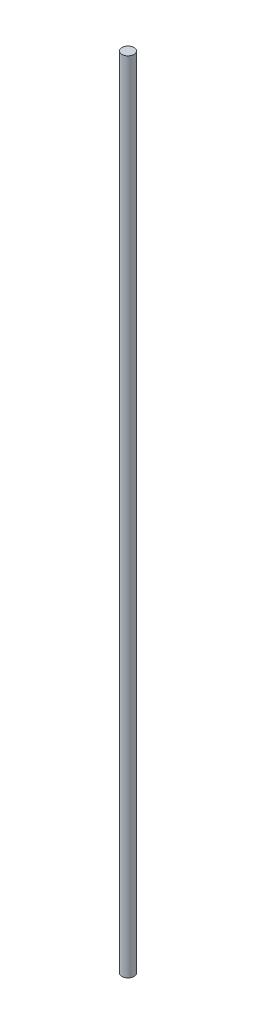
SolidWorks part; units mm, degrees
ref_plane "Plan de face" through (0, 0, 0) normal (0, 0, 1) x (1, 0, 0)
ref_plane "Plan de dessus" through (0, 0, 0) normal (0, 1, 0) x (1, 0, 0)
ref_plane "Plan de droite" through (0, 0, 0) normal (1, 0, 0) x (0, 0, -1)
sketch "Esquisse1" plane through (0, 0, 0) normal (0, 1, 0) x (1, 0, 0)
  circle A0 centre (0, 0) radius 2.5
  dimension "D1" = 5
extrude "Boss.-Extru.1" add sketch "Esquisse1" along normal up to surface (330.7 mm away)
